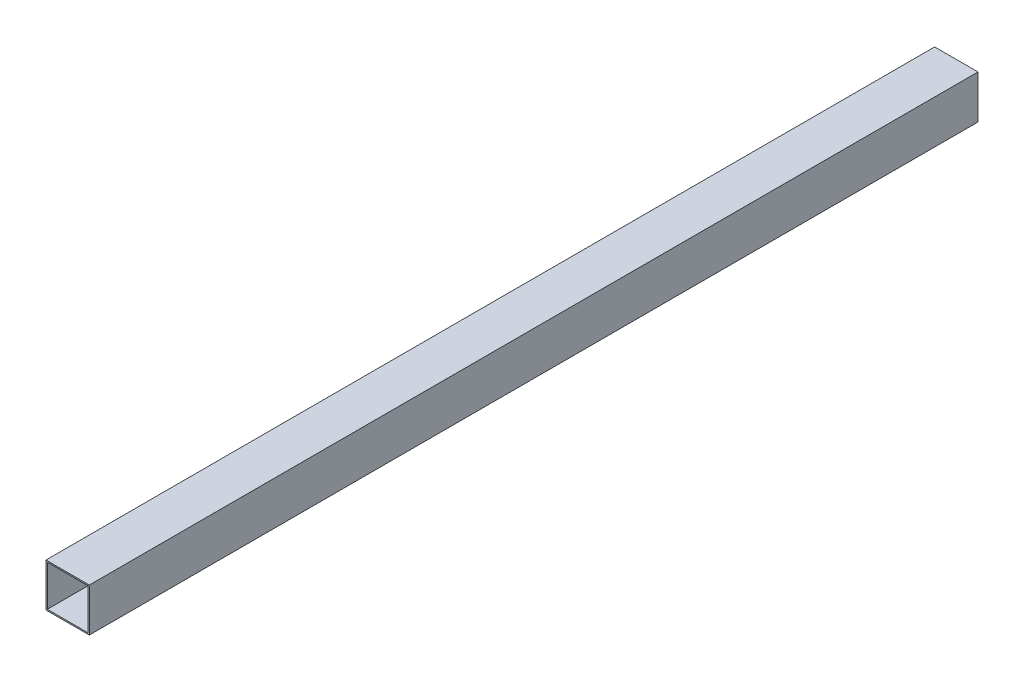
SolidWorks part; units mm, degrees
ref_plane "Front Plane" through (0, 0, 0) normal (0, 0, 1) x (1, 0, 0)
ref_plane "Top Plane" through (0, 0, 0) normal (0, 1, 0) x (1, 0, 0)
ref_plane "Right Plane" through (0, 0, 0) normal (1, 0, 0) x (0, 0, -1)
sketch "Sketch1" plane through (0, 0, 0) normal (0, 0, 1) x (1, 0, 0)
  line L0 (-18.8, 18.8) -> (18.8, 18.8)
  line L1 (-20, -20) -> (20, -20)
  line L2 (-20, -20) -> (-20, 20)
  line L3 (-20, 20) -> (20, 20)
  line L4 (20, -20) -> (20, 20)
  line L5 (-20, -20) -> (20, 20) construction
  line L6 (-20, 20) -> (20, -20) construction
  line L7 (18.8, -18.8) -> (18.8, 18.8)
  line L8 (-18.8, -18.8) -> (18.8, -18.8)
  line L9 (-18.8, -18.8) -> (-18.8, 18.8)
  point P0 (0, 0)
  dimension "D1" = 40
  dimension "D2" = 40
  dimension "D3" = 1.2
extrude "Boss-Extrude1" add sketch "Sketch1" along normal blind 820
